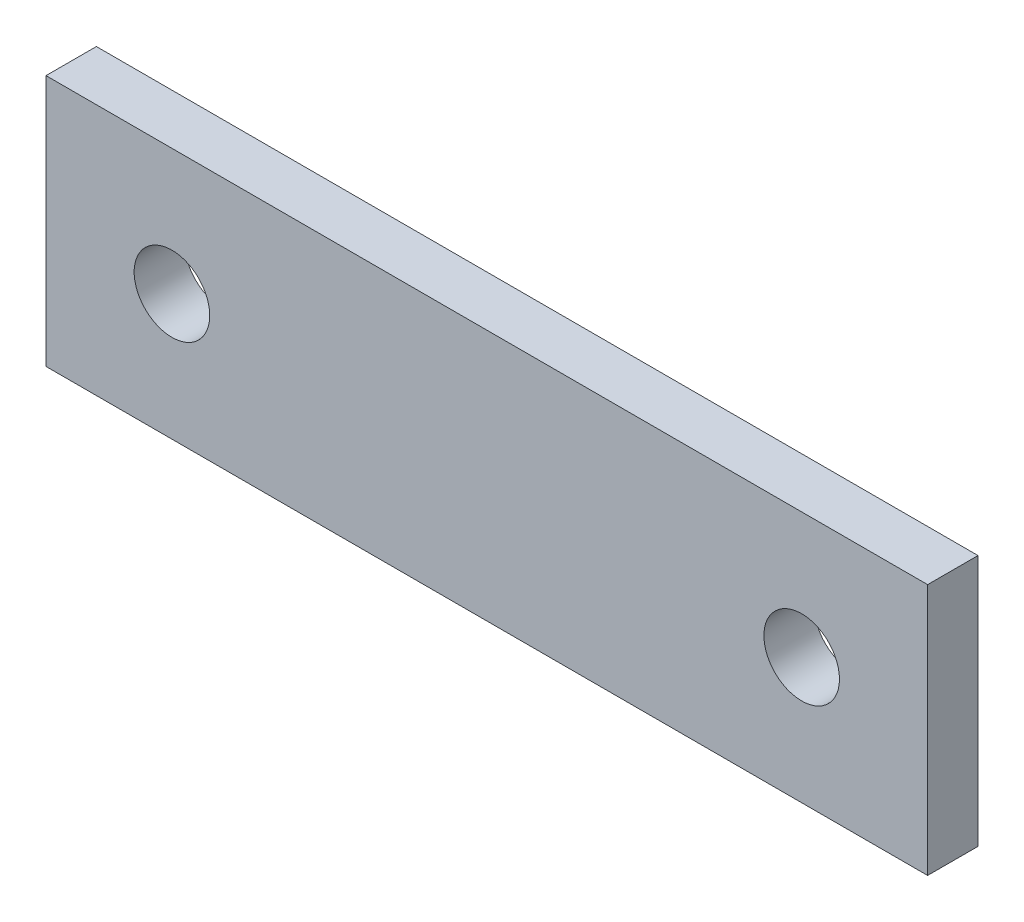
SolidWorks part; units mm, degrees
ref_plane "前视基准面" through (0, 0, 0) normal (0, 0, 1) x (1, 0, 0)
ref_plane "上视基准面" through (0, 0, 0) normal (0, 1, 0) x (1, 0, 0)
ref_plane "右视基准面" through (0, 0, 0) normal (1, 0, 0) x (0, 0, -1)
sketch "草图1" plane through (0, 0, 0) normal (0, 0, 1) x (1, 0, 0)
  line L0 (0, 5) -> (35, 5) construction
  line L1 (0, 0) -> (35, 0)
  line L2 (0, 0) -> (0, 10)
  line L3 (0, 10) -> (35, 10)
  line L4 (35, 0) -> (35, 10)
  circle A0 centre (5, 5) radius 1.5
  circle A1 centre (30, 5) radius 1.5
  dimension "D3" = 3
  dimension "D4" = 3
  dimension "D6" = 5
  dimension "D1" = 35
  dimension "D2" = 10
  dimension "D5" = 25
extrude "凸台-拉伸1" add sketch "草图1" along normal blind 2
